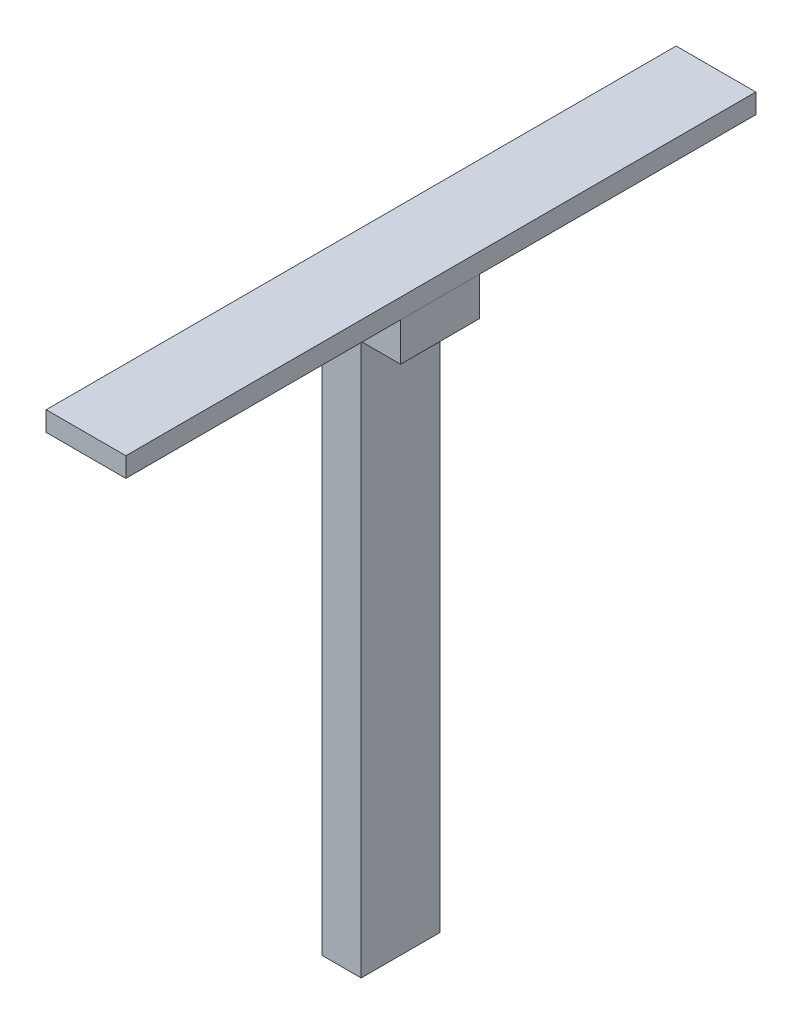
SolidWorks part; units mm, degrees
material "普通碳钢"
ref_plane "前视基准面" through (0, 0, 0) normal (0, 0, 1) x (1, 0, 0)
ref_plane "上视基准面" through (0, 0, 0) normal (0, 1, 0) x (1, 0, 0)
ref_plane "右视基准面" through (0, 0, 0) normal (1, 0, 0) x (0, 0, -1)
other "Configuration Table"
sketch3d "3D草图1"
  line L5 (0, 0, 0) -> (20, 0, 0)
  line L6 (0, 0, 0) -> (0, 0, 20)
  line L7 (0, 0, 20) -> (20, 0, 20)
  line L8 (20, 0, 0) -> (20, 0, 20)
  dimension "D1" = 20
  dimension "D2" = 20
extrude "凸台-拉伸1" add sketch "3D草图1" along direction (0, 1, 0) on the side of the normal blind 150 contours L6 L5 L8 L7
sketch "草图7" plane through (0, 0, 20) normal (0, 0, 1) x (1, 0, 0)
  line L1 (0, 150) -> (20.2325, 150)
  line L2 (0, 150) -> (0, 155)
  line L3 (0, 155) -> (20.2325, 155)
  line L4 (20.2325, 150) -> (20.2325, 155)
  dimension "D1" = 5
extrude "凸台-拉伸2" add sketch "草图7" along normal blind 70 and the other way blind 90 separate body
sketch "草图8" plane through (0, 0, 0) normal (0, -1, 0) x (-1, 0, 0)
  line L0 (0, 0) -> (-20, 0) construction
  line L1 (-20, -20) -> (-10, -20)
  line L2 (-20, -20) -> (-20, 0)
  line L3 (-20, 0) -> (-10, 0)
  line L4 (-10, -20) -> (-10, 0)
extrude "切除-拉伸1" cut sketch "草图8" against normal blind 140
